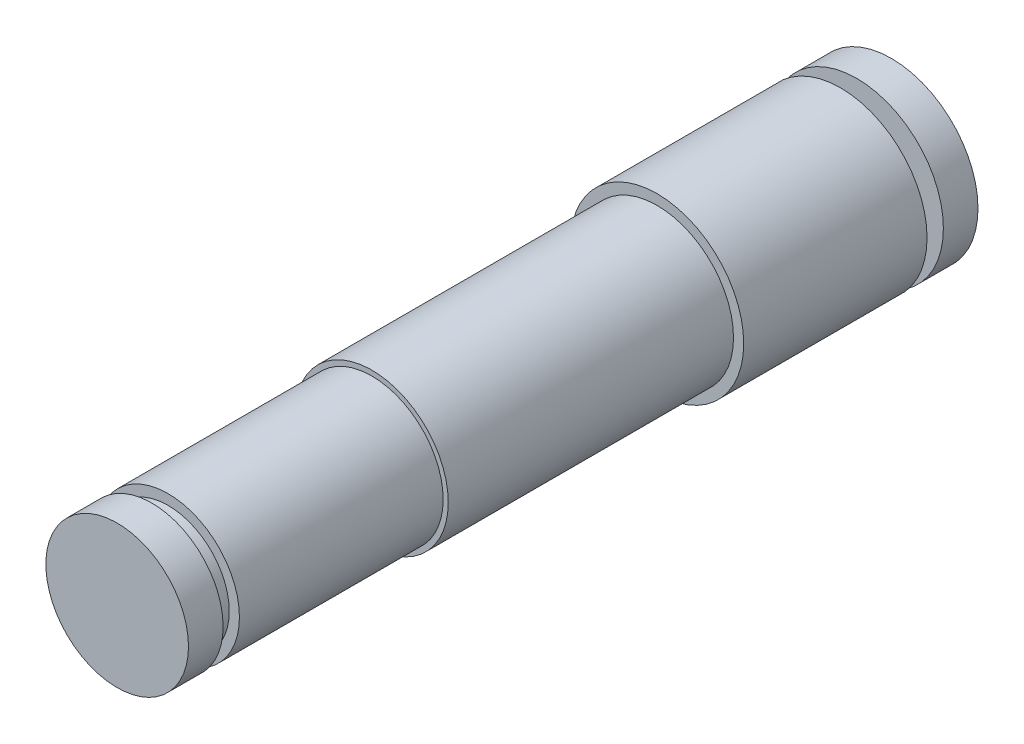
SolidWorks part; units mm, degrees
ref_plane "前视基准面" through (0, 0, 0) normal (0, 0, 1) x (1, 0, 0)
ref_plane "上视基准面" through (0, 0, 0) normal (0, 1, 0) x (1, 0, 0)
ref_plane "右视基准面" through (0, 0, 0) normal (1, 0, 0) x (0, 0, -1)
sketch "草图1" plane through (0, 0, 0) normal (0, 1, 0) x (1, 0, 0)
  line L0 (0, -1000) -> (0, 49000) construction
  line L1 (0, 0) -> (35, 0)
  line L2 (35, 0) -> (35, 17)
  line L3 (35, 17) -> (30, 17)
  line L4 (30, 17) -> (30, 25)
  line L5 (30, 25) -> (35, 25)
  line L6 (35, 25) -> (35, 125)
  line L7 (35, 125) -> (37.5, 125)
  line L8 (37.5, 125) -> (37.5, 265)
  line L9 (37.5, 265) -> (42.5, 265)
  line L10 (42.5, 265) -> (42.5, 355)
  line L11 (42.5, 355) -> (30.5, 355)
  line L12 (30.5, 355) -> (30.5, 363)
  line L13 (30.5, 363) -> (42.5, 363)
  line L14 (42.5, 363) -> (42.5, 380)
  line L15 (42.5, 380) -> (0, 380)
  line L16 (0, 380) -> (0, 0)
  dimension "D1" = 35
  dimension "D2" = 17
  dimension "D3" = 5
  dimension "D4" = 8
  dimension "D5" = 100
  dimension "D6" = 37.5
  dimension "D7" = 140
  dimension "D8" = 42.5
  dimension "D9" = 90
  dimension "D10" = 12
  dimension "D11" = 8
  dimension "D12" = 17
revolve "旋转1" add sketch "草图1" angle 360 about L0
